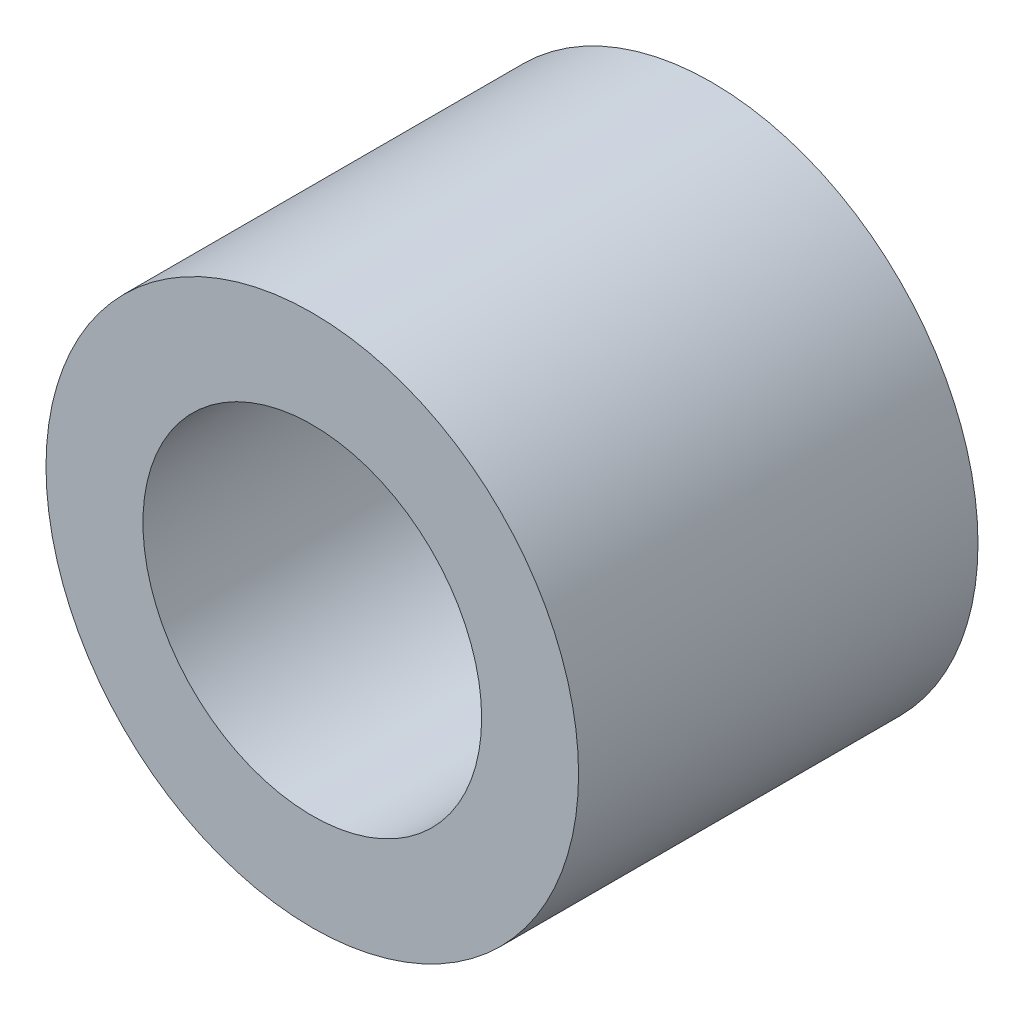
SolidWorks part; units mm, degrees
ref_plane "Front Plane" through (0, 0, 0) normal (0, 0, 1) x (1, 0, 0)
ref_plane "Top Plane" through (0, 0, 0) normal (0, 1, 0) x (1, 0, 0)
ref_plane "Right Plane" through (0, 0, 0) normal (1, 0, 0) x (0, 0, -1)
sketch "Sketch1" plane through (0, 0, 0) normal (0, 0, 1) x (1, 0, 0)
  circle A0 centre (0, 0) radius 25
  circle A1 centre (0, 0) radius 15.9
  dimension "D1" = 50
  dimension "D2" = 31.8
extrude "Boss-Extrude1" add sketch "Sketch1" along normal blind 37.5
